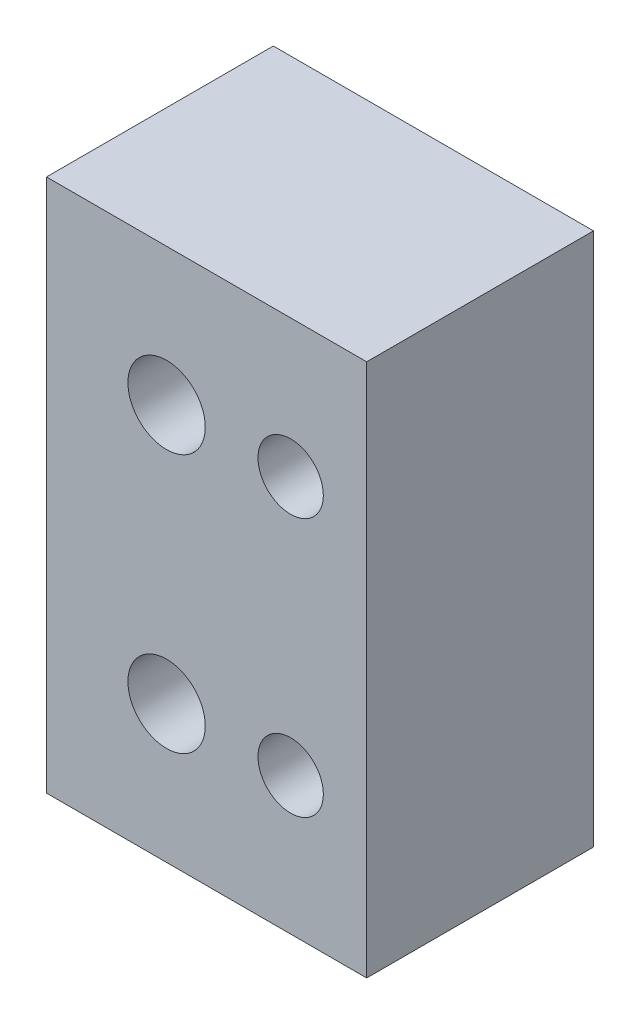
SolidWorks part; units mm, degrees
ref_plane "前视基准面" through (0, 0, 0) normal (0, 0, 1) x (1, 0, 0)
ref_plane "上视基准面" through (0, 0, 0) normal (0, 1, 0) x (1, 0, 0)
ref_plane "右视基准面" through (0, 0, 0) normal (1, 0, 0) x (0, 0, -1)
sketch "草图2" plane through (0, 0, 0) normal (0, 0, 1) x (1, 0, 0)
  line B0 (0, 0) -> (12, 0)
  line B1 (12, 20) -> (0, 20)
  line B2 (12, 0) -> (12, 20)
  line B3 (0, 0) -> (0, 20)
  circle B4 centre (9.15, 5.15) radius 1.25
  circle B5 centre (9.15, 14.85) radius 1.25
  circle B6 centre (4.5, 14.85) radius 1.5
  circle B7 centre (4.5, 5.15) radius 1.5
sketch_block_instance "块1-1"
sketch_block "块1"
sketch "草图3" plane through (0, 0, 0) normal (0, 0, 1) x (1, 0, 0)
  line L1 (0, 20) -> (12, 20)
  line L2 (0, 20) -> (0, 0)
  line L3 (0, 0) -> (12, 0)
  line L4 (12, 20) -> (12, 0)
  circle A0 centre (4.5, 14.85) radius 1.45
  circle A1 centre (4.5, 5.15) radius 1.45
  circle A2 centre (9.15, 14.85) radius 1.225
  circle A3 centre (9.15, 5.15) radius 1.225
  dimension "D1" = 2.45
  dimension "D2" = 2.9
extrude "凸台-拉伸1" add sketch "草图3" along normal blind 8.5
